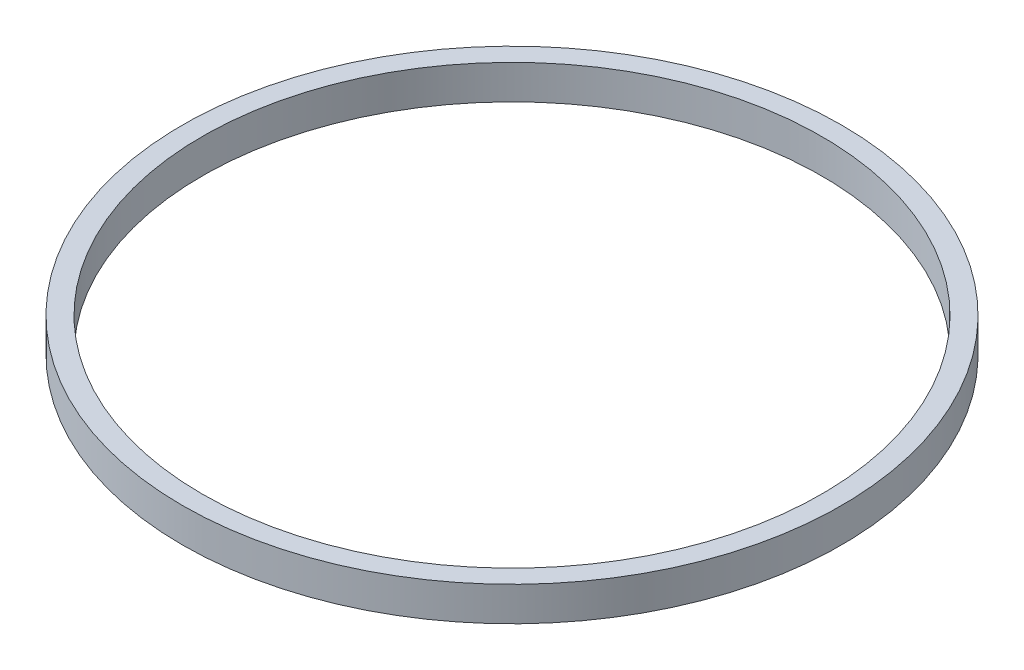
SolidWorks part; units mm, degrees
material "Pine"
ref_plane "Front Plane" through (0, 0, 0) normal (0, 0, 1) x (1, 0, 0)
ref_plane "Top Plane" through (0, 0, 0) normal (0, 1, 0) x (1, 0, 0)
ref_plane "Right Plane" through (0, 0, 0) normal (1, 0, 0) x (0, 0, -1)
sketch "Sketch1" plane through (0, 0, 0) normal (0, 1, 0) x (1, 0, 0)
  circle A0 centre (0, 0) radius 172
  circle A1 centre (0, 0) radius 183
  dimension "D1" = 366
  dimension "D2" = 344
extrude "Boss-Extrude1" add sketch "Sketch1" along normal mid plane 19
